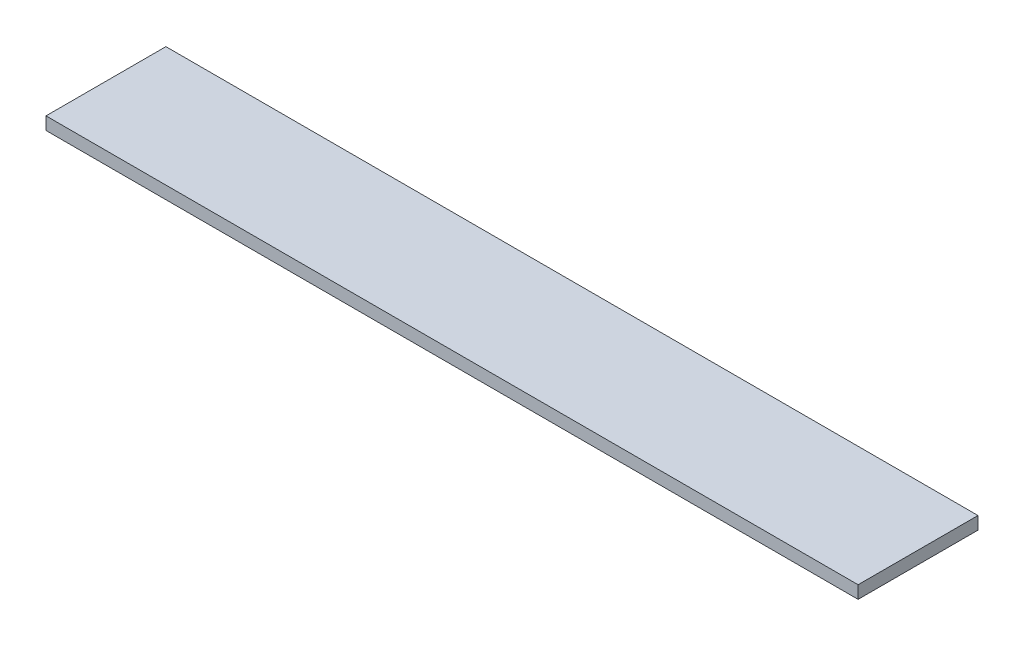
SolidWorks part; units mm, degrees
ref_plane "Front" through (0, 0, 0) normal (0, 0, 1) x (1, 0, 0)
ref_plane "Top" through (0, 0, 0) normal (0, 1, 0) x (1, 0, 0)
ref_plane "Right" through (0, 0, 0) normal (1, 0, 0) x (0, 0, -1)
sketch "Sketch1" plane through (0, 0, 0) normal (0, 1, 0) x (1, 0, 0)
  line L1 (0, 0) -> (203.2, 0)
  line L2 (0, 0) -> (0, 30)
  line L3 (0, 30) -> (203.2, 30)
  line L4 (203.2, 0) -> (203.2, 30)
  dimension "D1" = 203.2
  dimension "D2" = 30
extrude "Boss-Extrude1" add sketch "Sketch1" along normal blind 3.175
